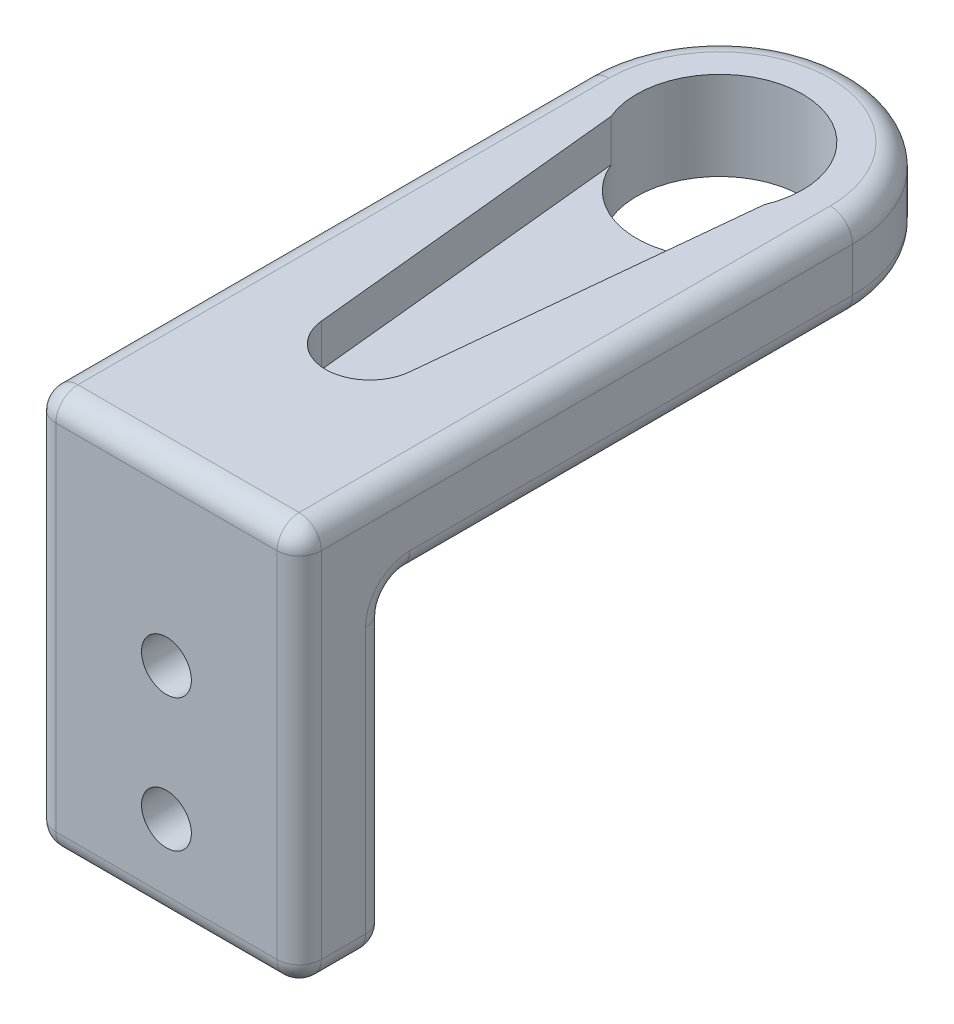
SolidWorks part; units mm, degrees
ref_plane "Front Plane" through (0, 0, 0) normal (0, 0, 1) x (1, 0, 0)
ref_plane "Top Plane" through (0, 0, 0) normal (0, 1, 0) x (1, 0, 0)
ref_plane "Right Plane" through (0, 0, 0) normal (1, 0, 0) x (0, 0, -1)
sketch "Sketch1" plane through (0, 0, 0) normal (0, 1, 0) x (1, 0, 0)
  line L1 (-6, 0) -> (0, 0) construction
  line L4 (-6, 0) -> (-6, -25)
  line L5 (-6, -25) -> (6, -25)
  line L6 (6, -25) -> (6, 0)
  arc A1 (-6, 0) -> (6, 0) centre (0, 0) cw
  dimension "D3" = 6
  dimension "D1" = 6
  dimension "D2" = 25
extrude "Yaw Arm Base" add sketch "Sketch1" along normal blind 4
sketch "Sketch2" plane through (0, 4, 0) normal (0, 1, 0) x (1, 0, 0)
  circle A0 centre (0, 0) radius 3.75
  dimension "D1" = 7.5
extrude "Yaw Arm Mounting Hole" cut sketch "Sketch2" against normal up to next
sketch "Sketch4" plane through (0, 4, 0) normal (0, 1, 0) x (1, 0, 0)
  line L0 (-3.46, -1.446) -> (-1.9899, -16.006)
  line L1 (3.46, -1.446) -> (1.9899, -16.006)
  line L4 (-6, 0) -> (-6, -25) construction
  line L5 (0, -15.8051) -> (0, 0) construction
  arc A0 (-1.9899, -16.006) -> (1.9899, -16.006) centre (0, -15.8051) ccw
  arc A1 (-3.46, -1.446) -> (3.46, -1.446) centre (0, 0) ccw
  circle A2 centre (0, 0) radius 3.75 construction
  dimension "D3" = 2
  dimension "D1" = 14.56
  dimension "D2" = 2.54
extrude "Yaw Arm Slot" cut sketch "Sketch4" against normal blind 1.9
sketch "Sketch5" plane through (0, 0, 0) normal (0, -1, 0) x (1, 0, 0)
  line L1 (-6, 25) -> (6, 25)
  line L2 (-6, 25) -> (-6, 21)
  line L3 (-6, 21) -> (6, 21)
  line L4 (6, 25) -> (6, 21)
  point P5 (0, 0)
  dimension "D1" = 4
extrude "Mounting Bracket" add sketch "Sketch5" along normal blind 14
sketch "Sketch8" plane through (0, 0, 21) normal (0, 0, -1) x (-1, 0, 0)
  line L0 (0, 0) -> (0, -14) construction
  line L1 (6, -14) -> (-6, -14) construction
  line L2 (-6, 0) -> (6, 0) construction
  circle A0 centre (0, -10) radius 1.125
  circle A1 centre (0, -4) radius 1.125
  dimension "D1" = 2.25
  dimension "D2" = 2.25
  dimension "D3" = 4
  dimension "D4" = 4
extrude "Bracket Mounting Holes" cut sketch "Sketch8" against normal up to next
fillet "1mm Fillets" radius 1 16 edges at (6, -7, 21) (-6, -7, 21) (6, 4, 12.5) (0, 4, -6) (6, 0, 10.5) (0, 0, -6) (0, 4, 25) (6, -5, 25) (-6, -5, 25) (0, -14, 25) (6, -14, 23) (0, -14, 21) (-6, -14, 23) (-6, 4, 12.5) (-6, 0, 10.5) (0, 0, 21)
